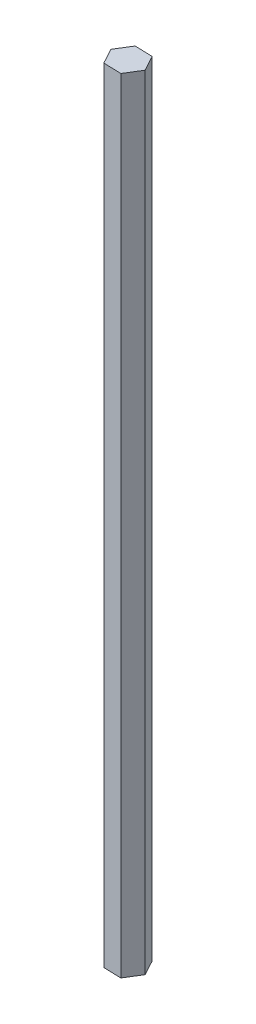
SolidWorks part; units mm, degrees
ref_plane "Front Plane" through (0, 0, 0) normal (0, 0, 1) x (1, 0, 0)
ref_plane "Top Plane" through (0, 0, 0) normal (0, 1, 0) x (1, 0, 0)
ref_plane "Right Plane" through (0, 0, 0) normal (1, 0, 0) x (0, 0, -1)
sketch "Sketch1" plane through (0, 0, 0) normal (0, 1, 0) x (1, 0, 0)
  line L1 (1.8613, -3.4567) -> (3.9243, -0.1164)
  line L2 (3.9243, -0.1164) -> (2.0629, 3.3403)
  line L3 (2.0629, 3.3403) -> (-1.8613, 3.4567)
  line L4 (-1.8613, 3.4567) -> (-3.9243, 0.1164)
  line L5 (-3.9243, 0.1164) -> (-2.0629, -3.3403)
  line L6 (-2.0629, -3.3403) -> (1.8613, -3.4567)
  circle A0 centre (0, 0) radius 3.4 construction
  dimension "D1" = 6.8
extrude "Boss-Extrude1" add sketch "Sketch1" along normal blind 175
